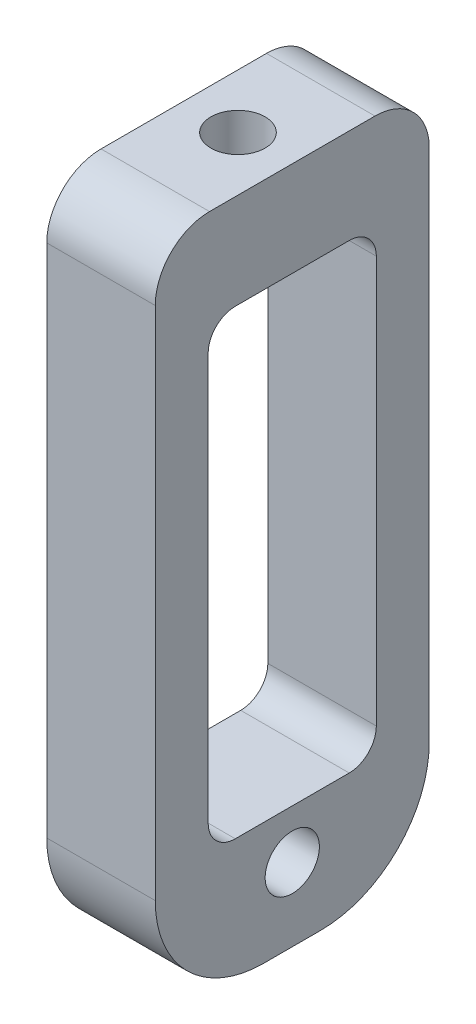
SolidWorks part; units mm, degrees
other "Markup1"
sketch "Sketch6" plane through (-4, 8, -3.5) normal (-0.1216, 0.9914, -0.0475) x (-0.0131, 0.0463, 0.9988)
sketch "Sketch19" plane through (-2.475, 25, -7.5) normal (-0.1216, 0.9914, -0.0475) x (-0.0131, 0.0463, 0.9988)
sketch "Sketch20" plane through (-2.475, 25, -7.5) normal (-0.1216, 0.9914, -0.0475) x (-0.0131, 0.0463, 0.9988)
sketch "Sketch25" plane through (-2, 25, -5.05) normal (-0.1216, 0.9914, -0.0475) x (-0.0131, 0.0463, 0.9988)
sketch "Sketch26" plane through (-2, 25, -5.05) normal (-0.1216, 0.9914, -0.0475) x (-0.0131, 0.0463, 0.9988)
sketch "Sketch27" [suppressed] plane through (-2.475, 25, -7.5) normal (-0.1216, 0.9914, -0.0475) x (-0.0131, 0.0463, 0.9988)
sketch "Sketch28" plane through (-2.475, 25, -7.5) normal (-0.1216, 0.9914, -0.0475) x (-0.0131, 0.0463, 0.9988)
material "7075 T651 protolabs"
ref_plane "Front Plane" through (0, 0, 0) normal (0, 0, 1) x (1, 0, 0)
ref_plane "Top Plane" through (0, 0, 0) normal (0, 1, 0) x (1, 0, 0)
ref_plane "Right Plane" through (0, 0, 0) normal (1, 0, 0) x (0, 0, -1)
sketch "Sketch16" plane through (0, 0, 0) normal (0, 1, 0) x (1, 0, 0)
  line L1 (-2.475, -7.5) -> (2.475, -7.5)
  line L2 (-2.475, -7.5) -> (-2.475, 7.5)
  line L3 (-2.475, 7.5) -> (2.475, 7.5)
  line L4 (2.475, -7.5) -> (2.475, 7.5)
  line L5 (-2.475, -7.5) -> (2.475, 7.5) construction
  line L6 (-2.475, 7.5) -> (2.475, -7.5) construction
  point P0 (0, 0)
  dimension "D1" = 15
  dimension "D2" = 4.95
extrude "Main Extrude_Locking" [suppressed] add sketch "Sketch16" along normal blind 25
sketch "Sketch18" [suppressed] plane through (-2.475, 0, 0) normal (-1, 0, 0) x (0, 0, 1)
  line L0 (0, 0) -> (0, 2.5) construction
  line L1 (-7.5, 0) -> (7.5, 0) construction
  circle A0 centre (0, 3.7) radius 1.2
  dimension "D2" = 2.4
  dimension "D1" = 2.5
extrude "Cut-Extrude1" [suppressed] cut sketch "Sketch18" against normal up to surface (4.95 mm away)
sketch "Sketch8" [suppressed] plane through (-2.475, 0, 0) normal (-1, 0, 0) x (0, 0, 1)
  line L0 (0, 4.9) -> (-7.5, 4.9) construction
  line L1 (-7.5, 25) -> (-7.5, 0) construction
  line L3 (5, 5.9) -> (-5, 5.9)
  line L4 (5, 5.9) -> (5, 18.9)
  line L5 (5, 18.9) -> (-5, 18.9)
  line L6 (-5, 5.9) -> (-5, 18.9)
  line L7 (5, 5.9) -> (-5, 18.9) construction
  line L8 (5, 18.9) -> (-5, 5.9) construction
  circle A0 centre (0, 3.7) radius 1.2 construction
  point P6 (0, 12.4)
  dimension "D1" = 2
  dimension "D2" = 13
  dimension "D3" = 10
extrude "Cut-Extrude2" [suppressed] cut sketch "Sketch8" against normal up to surface (4.95 mm away)
sketch "Sketch9" [suppressed] plane through (0, 25, 0) normal (0, 1, 0) x (1, 0, 0)
  circle A0 centre (0, 0) radius 1.35
  dimension "D1" = 2.7
extrude "Cut-Extrude3" [suppressed] cut sketch "Sketch9" against normal up to surface (6.1 mm away)
fillet "Fillet1" [suppressed] radius 5
fillet "Fillet2" [suppressed] radius 3
fillet "Fillet3" [suppressed] radius 0.5
sketch "Sketch21" plane through (0, 0, 0) normal (0, 1, 0) x (1, 0, 0)
  line L1 (-2, -5.05) -> (2, -5.05)
  line L2 (-2, -5.05) -> (-2, 5.05)
  line L3 (-2, 5.05) -> (2, 5.05)
  line L4 (2, -5.05) -> (2, 5.05)
  line L5 (-2, -5.05) -> (2, 5.05) construction
  line L6 (-2, 5.05) -> (2, -5.05) construction
  point P0 (0, 0)
  dimension "D1" = 4
  dimension "D2" = 10.1
extrude "Boss-Extrude1" add sketch "Sketch21" along normal blind 25
sketch "Sketch22" plane through (-2, 0, 0) normal (-1, 0, 0) x (0, 0, 1)
  line L0 (-5.05, 0) -> (5.05, 0) construction
  circle A0 centre (0, 2.7) radius 1
  point P4 (0, 0)
  dimension "D1" = 2
  dimension "D2" = 2.7
extrude "Cut-Extrude4" cut sketch "Sketch22" against normal up to surface (4 mm away) up to face at (2, 12.5, 0)
sketch "Sketch23" plane through (-2, 0, 0) normal (-1, 0, 0) x (0, 0, 1)
  line L0 (-5.05, 0) -> (5.05, 0) construction
  line L1 (3.1, 4.5) -> (-3.1, 4.5)
  line L2 (3.1, 4.5) -> (3.1, 21.5)
  line L3 (3.1, 21.5) -> (-3.1, 21.5)
  line L4 (-3.1, 4.5) -> (-3.1, 21.5)
  line L5 (-5.05, 25) -> (5.05, 25) construction
  point P8 (0, 4.5)
  dimension "D1" = 4.5
  dimension "D2" = 3.5
  dimension "D3" = 6.2
extrude "Cut-Extrude5" cut sketch "Sketch23" against normal up to surface (4 mm away) up to face at (2, 2.7, 1)
sketch "Sketch24" plane through (0, 25, 0) normal (0, 1, 0) x (1, 0, 0)
  circle A0 centre (0, 0) radius 1
  dimension "D1" = 2
extrude "Cut-Extrude6" cut sketch "Sketch24" against normal up to surface (3.5 mm away) up to face at (0, 21.5, 0)
fillet "Fillet4" radius 4 2 edges at (0, 0, 5.05) (0, 0, -5.05)
fillet "Fillet5" radius 2 2 edges at (0, 25, -5.05) (0, 25, 5.05)
fillet "Fillet6" radius 1 4 edges at (0, 4.5, 3.1) (0, 4.5, -3.1) (0, 21.5, -3.1) (0, 21.5, 3.1)
